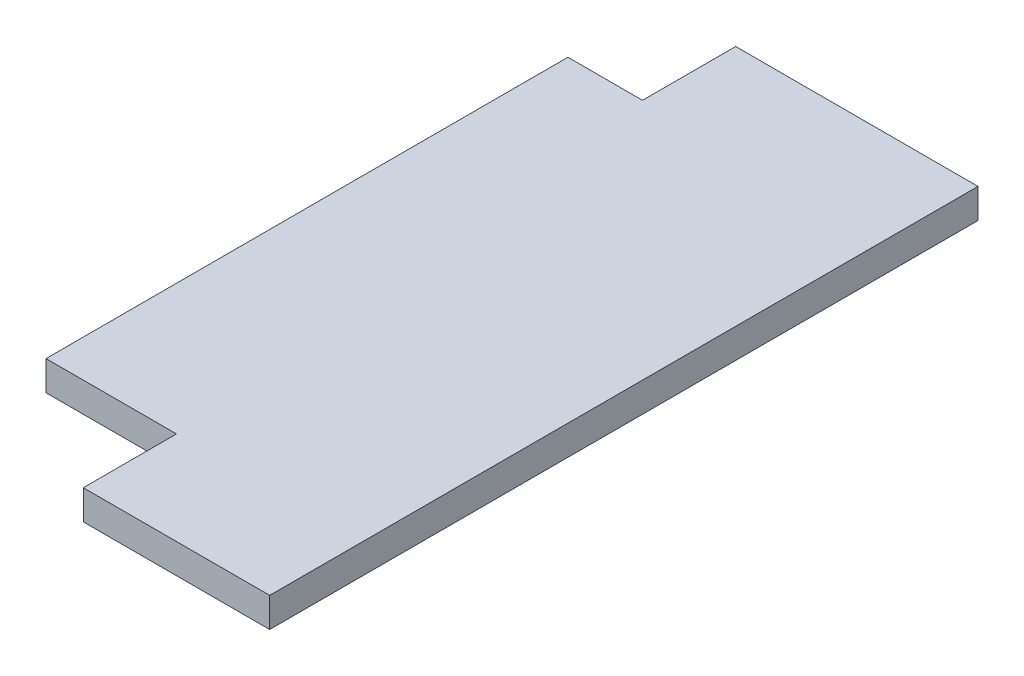
SolidWorks part; units mm, degrees
ref_plane "Front Plane" through (0, 0, 0) normal (0, 0, 1) x (1, 0, 0)
ref_plane "Top Plane" through (0, 0, 0) normal (0, 1, 0) x (1, 0, 0)
ref_plane "Right Plane" through (0, 0, 0) normal (1, 0, 0) x (0, 0, -1)
sketch "Sketch1" plane through (0, 0, 0) normal (0, 1, 0) x (1, 0, 0)
  line L0 (0, 0) -> (0, 38)
  line L1 (0, 38) -> (-13, 38)
  line L2 (-13, 38) -> (-13, 33)
  line L3 (-13, 33) -> (-17, 33)
  line L4 (-17, 33) -> (-17, 5)
  line L5 (-17, 5) -> (-10, 5)
  line L6 (-10, 5) -> (-10, 0)
  line L7 (-10, 0) -> (0, 0)
  dimension "D1" = 38
  dimension "D2" = 17
  dimension "D3" = 10
  dimension "D4" = 13
  dimension "D5" = 5
  dimension "D6" = 5
extrude "Boss-Extrude1" add sketch "Sketch1" along normal blind 1.5875
